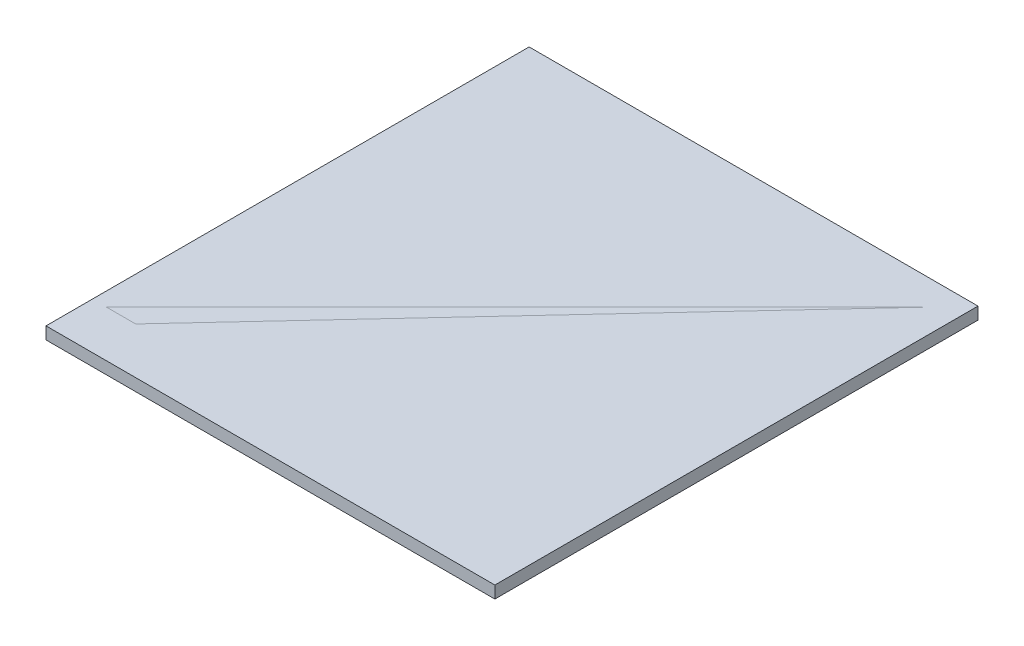
SolidWorks part; units mm, degrees
ref_plane "Front Plane" through (0, 0, 0) normal (0, 0, 1) x (1, 0, 0)
ref_plane "Top Plane" through (0, 0, 0) normal (0, 1, 0) x (1, 0, 0)
ref_plane "Right Plane" through (0, 0, 0) normal (1, 0, 0) x (0, 0, -1)
sketch "Sketch1" plane through (0, 0, 0) normal (0, 1, 0) x (1, 0, 0)
  line L1 (0, 0) -> (29.46, 0)
  line L2 (0, 0) -> (0, 31.71)
  line L3 (0, 31.71) -> (29.46, 31.71)
  line L4 (29.46, 0) -> (29.46, 31.71)
  dimension "D1" = 29.46
  dimension "D2" = 31.71
extrude "Boss-Extrude1" add sketch "Sketch1" along normal blind 0.8
ref_plane "Plane1" through (0, 0.8, 0) normal (0, 1, 0) x (1, 0, 0)
sketch "Sketch2" plane through (0, 0.8, 0) normal (0, 1, 0) x (1, 0, 0)
  line L0 (29.46, 0) -> (29.46, 31.71) construction
  line L1 (0.9, 30.71) -> (28.56, 30.71)
  line L2 (0.9, 30.71) -> (0.9, 3.05)
  line L3 (0.9, 3.05) -> (28.56, 3.05)
  line L4 (28.56, 30.71) -> (28.56, 3.05)
  line L5 (29.46, 31.71) -> (0, 31.71) construction
  dimension "D1" = 27.66
  dimension "D2" = 27.66
  dimension "D3" = 0.9
  dimension "D4" = 1
surface "Surface-Fill1" sketch "Sketch2"
sketch "Sketch3" plane through (0, 0.8, 0) normal (0, 1, 0) x (1, 0, 0)
  line L0 (0, 0) -> (29.46, 0) construction
  line L1 (8.48, 0) -> (20.98, 0)
  line L2 (8.48, 0) -> (8.48, 1.25)
  line L3 (8.48, 1.25) -> (20.98, 1.25)
  line L4 (20.98, 0) -> (20.98, 1.25)
  point P6 (14.73, 1.25)
  dimension "D1" = 12.5
  dimension "D2" = 14.73
surface "Surface-Fill2" sketch "Sketch3"
